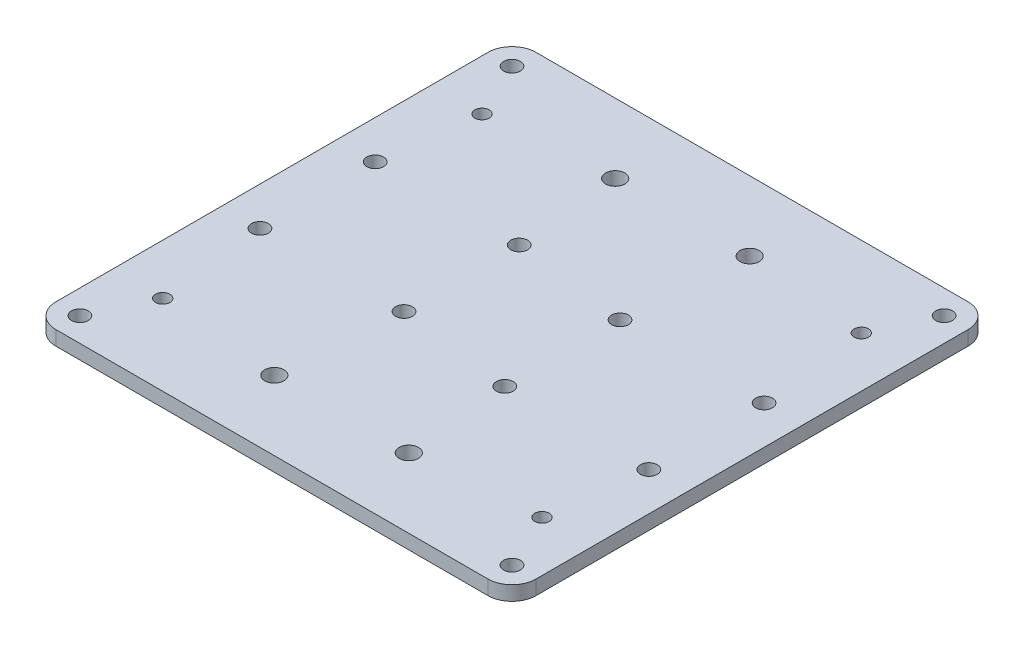
SolidWorks part; units mm, degrees
material "普通碳钢"
ref_plane "前视基准面" through (0, 0, 0) normal (0, 0, 1) x (1, 0, 0)
ref_plane "上视基准面" through (0, 0, 0) normal (0, 1, 0) x (1, 0, 0)
ref_plane "右视基准面" through (0, 0, 0) normal (1, 0, 0) x (0, 0, -1)
sketch "草图1" plane through (0, 0, 0) normal (0, 1, 0) x (1, 0, 0)
  line L1 (-45, 50) -> (45, 50)
  line L2 (-50, 45) -> (-50, -45)
  line L3 (-45, -50) -> (45, -50)
  line L4 (50, 45) -> (50, -45)
  line L5 (-50, 50) -> (50, -50) construction
  line L6 (-50, -50) -> (50, 50) construction
  arc A0 (50, -45) -> (45, -50) centre (45, -45) cw
  arc A1 (-45, -50) -> (-50, -45) centre (-45, -45) cw
  arc A2 (45, 50) -> (50, 45) centre (45, 45) cw
  arc A3 (-50, 45) -> (-45, 50) centre (-45, 45) cw
  circle A4 centre (-45, 45) radius 1.75
  circle A5 centre (45, 45) radius 1.75
  circle A6 centre (-45, -45) radius 1.75
  circle A7 centre (45, -45) radius 1.75
  circle A8 centre (12, 10.5) radius 1.75
  circle A9 centre (42, 10.5) radius 1.75
  circle A10 centre (12, -13.5) radius 1.75
  circle A11 centre (42, -13.5) radius 1.75
  circle A12 centre (-42, 13.5) radius 1.75
  circle A13 centre (-12, 13.5) radius 1.75
  circle A14 centre (-42, -10.5) radius 1.75
  circle A15 centre (-12, -10.5) radius 1.75
  circle A16 centre (-14, -35.5) radius 2
  circle A17 centre (14, -35.5) radius 2
  circle A18 centre (-14, 35.5) radius 2
  circle A19 centre (14, 35.5) radius 2
  circle A20 centre (-39.5, 33.25) radius 1.5
  circle A21 centre (39.5, 33.25) radius 1.5
  circle A22 centre (-39.5, -33.25) radius 1.5
  circle A23 centre (39.5, -33.25) radius 1.5
  point P0 (0, 0)
  point P8 (0, 50)
  point P11 (0, -50)
  dimension "D2" = 5
  dimension "D3" = 100
  dimension "D8" = 39.5
  dimension "D4" = 12
  dimension "D10" = 4
  dimension "D12" = 4
  dimension "D16" = 14
  dimension "D19" = 79
  dimension "D1" = 100
  dimension "D5" = 12
  dimension "D6" = 30
  dimension "D7" = 24
  dimension "D9" = 24
  dimension "D11" = 39.5
  dimension "D13" = 14
  dimension "D14" = 28
  dimension "D15" = 14.5
  dimension "D17" = 28
  dimension "D18" = 14.5
  dimension "D20" = 66.5
  dimension "D21" = 33.25
  dimension "D22" = 39.5
extrude "凸台-拉伸1" add sketch "草图1" along normal blind 3
